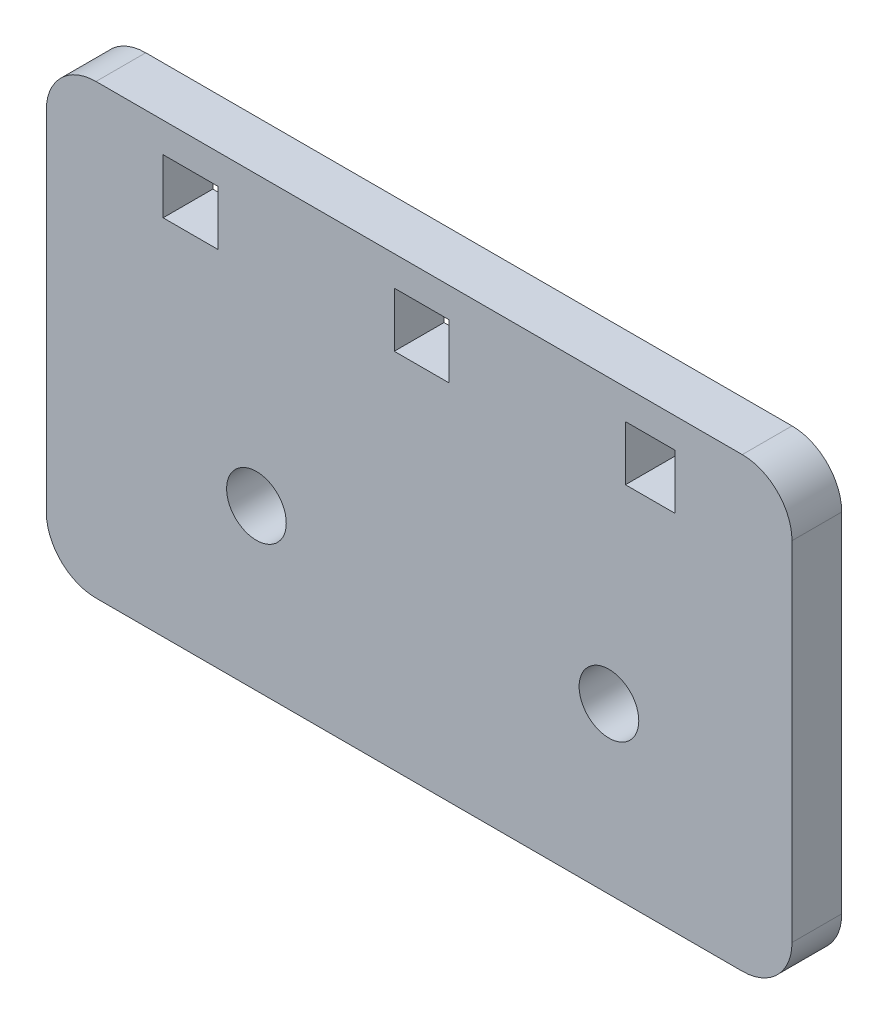
SolidWorks part; units mm, degrees
ref_plane "前视基准面" through (0, 0, 0) normal (0, 0, 1) x (1, 0, 0)
ref_plane "上视基准面" through (0, 0, 0) normal (0, 1, 0) x (1, 0, 0)
ref_plane "右视基准面" through (0, 0, 0) normal (1, 0, 0) x (0, 0, -1)
sketch "草图1" plane through (0, 0, 0) normal (0, 0, 1) x (1, 0, 0)
  line L1 (0, 0) -> (75, 0)
  line L2 (0, 0) -> (0, -45)
  line L3 (0, -45) -> (75, -45)
  line L4 (75, 0) -> (75, -45)
  circle A5 centre (21.135, -28.9) radius 3 construction
  circle A6 centre (56.59, -28.4) radius 3 construction
  circle A7 centre (21.135, -28.9) radius 3
  circle A8 centre (56.59, -28.4) radius 3
  dimension "D1" = 45
  dimension "D2" = 75
  dimension "D3" = 35.455
extrude "凸台-拉伸1" add sketch "草图1" along normal blind 5
sketch "草图2" plane through (0, 0, 5) normal (0, 0, 1) x (1, 0, 0)
  line L0 (0, 0) -> (0, -3) construction
  line L1 (0, 0) -> (0, -45) construction
  line L2 (0, -3) -> (75, -3) construction
  line L3 (75, -45) -> (75, 0) construction
  line L4 (75, -3) -> (75, -8.5) construction
  line L5 (75, -8.5) -> (0, -8.5) construction
  line L6 (0, -8.5) -> (0, -3) construction
  line L7 (0, -8.5) -> (11.75, -8.5) construction
  line L8 (11.75, -8.5) -> (11.75, -3)
  line L9 (11.75, -3) -> (17.25, -3)
  line L10 (17.25, -3) -> (17.25, -8.5)
  line L11 (17.25, -8.5) -> (11.75, -8.5)
  line L12 (37.5, -3) -> (35, -3)
  line L13 (35, -3) -> (35, -8.5)
  line L14 (35, -8.5) -> (40.5, -8.5)
  line L15 (40.5, -8.5) -> (40.5, -3)
  line L16 (40.5, -3) -> (37.5, -3)
  line L17 (75, -8.5) -> (63.25, -8.5)
  line L18 (63.25, -8.5) -> (63.25, -3)
  line L19 (63.25, -3) -> (58.25, -3)
  line L20 (58.25, -3) -> (58.25, -8.5)
  line L21 (58.25, -8.5) -> (63.25, -8.5)
  dimension "D1" = 3
  dimension "D2" = 5.5
  dimension "D3" = 11.75
  dimension "D4" = 5.5
  dimension "D5" = 2.5
  dimension "D6" = 5.5
  dimension "D7" = 11.75
  dimension "D8" = 5
extrude "切除-拉伸1" cut sketch "草图2" against normal blind 5 contours L15 L16 L12 L13 L14 | L20 L21 L18 L19 | L11 L10 L9 L8
fillet "圆角1" radius 5 4 edges at (0, -45, 2.5) (75, -45, 2.5) (75, 0, 2.5) (0, 0, 2.5)
